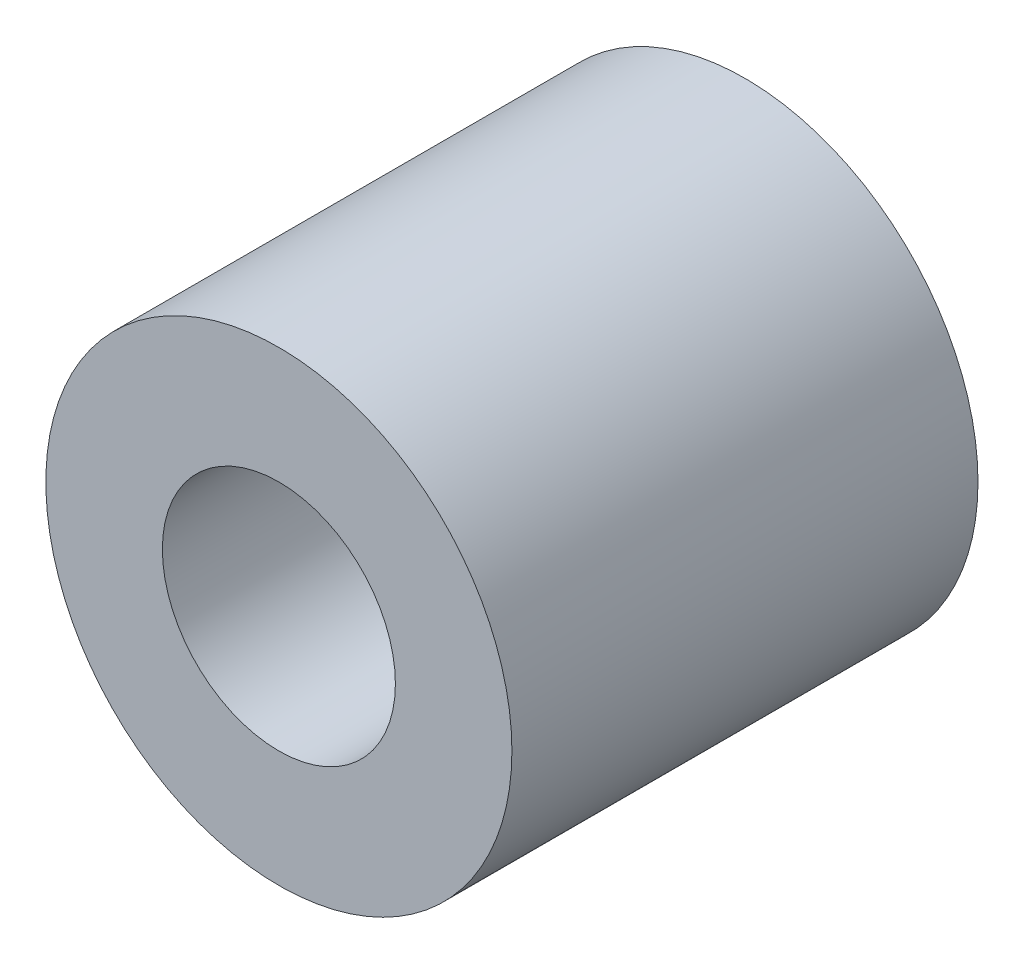
SolidWorks part; units mm, degrees
ref_plane "정면" through (0, 0, 0) normal (0, 0, 1) x (1, 0, 0)
ref_plane "윗면" through (0, 0, 0) normal (0, 1, 0) x (1, 0, 0)
ref_plane "우측면" through (0, 0, 0) normal (1, 0, 0) x (0, 0, -1)
sketch "스케치1" plane through (0, 0, 0) normal (0, 0, 1) x (1, 0, 0)
  circle A0 centre (0, 0) radius 10
  circle A1 centre (0, 0) radius 20
  dimension "D1" = 40
  dimension "D2" = 20
extrude "보스-돌출3" add sketch "스케치1" along normal blind 40
